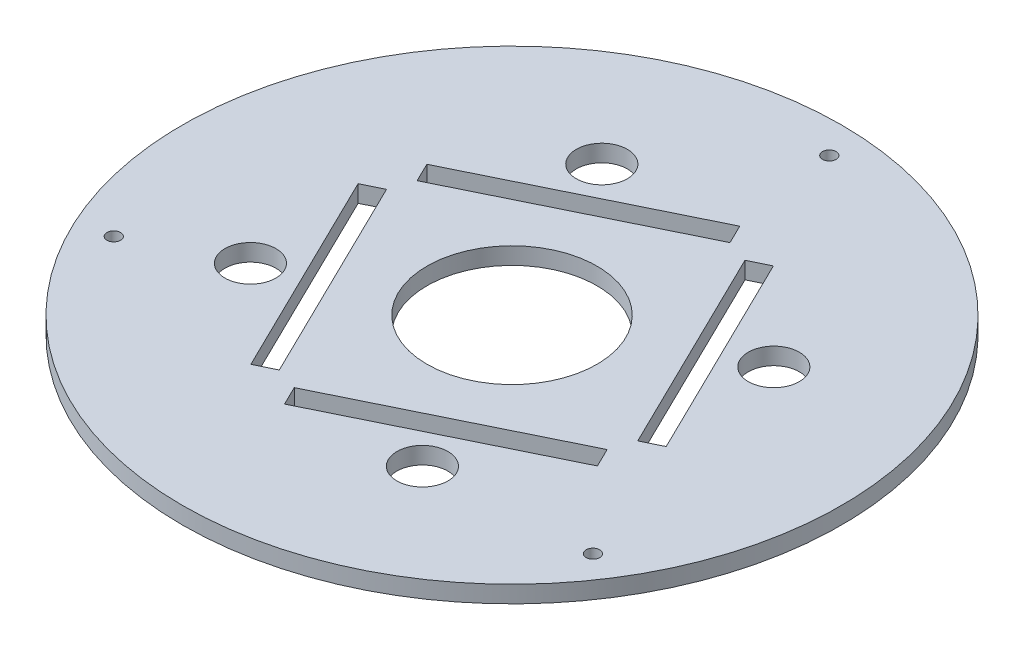
SolidWorks part; units mm, degrees
ref_plane "前视基准面" through (0, 0, 0) normal (0, 0, 1) x (1, 0, 0)
ref_plane "上视基准面" through (0, 0, 0) normal (0, 1, 0) x (1, 0, 0)
ref_plane "右视基准面" through (0, 0, 0) normal (1, 0, 0) x (0, 0, -1)
sketch "草图1" plane through (0, 0, 0) normal (0, 1, 0) x (1, 0, 0)
  circle A0 centre (0, 0) radius 77.5
  circle A1 centre (4.7844, 69.8363) radius 1.6
  circle A2 centre (-62.8722, -30.7747) radius 1.6
  circle A3 centre (58.0878, -39.0616) radius 1.6
  dimension "D1" = 155
extrude "凸台-拉伸1" add sketch "草图1" along normal blind 4
sketch "草图3" plane through (0, 4, 0) normal (0, 1, 0) x (1, 0, 0)
  circle A0 centre (0, 0) radius 20
  dimension "D1" = 40
extrude "切除-拉伸2" cut sketch "草图3" against normal through all both and the other way through all
sketch "草图4" plane through (0, 0, 0) normal (0, -1, 0) x (1, 0, 0)
  line L0 (0.002, -0.0288) -> (41.318, -20.2522) construction
  line L1 (0.002, -0.0288) -> (20.2254, 41.2872) construction
  line L2 (38.5519, 16.1767) -> (40.7501, 20.6676)
  line L3 (40.7501, 20.6676) -> (-8.6495, 44.8477)
  line L4 (-8.6495, 44.8477) -> (-10.8477, 40.3568)
  line L5 (-10.8477, 40.3568) -> (38.5519, 16.1767)
  line L6 (16.0503, 32.7576) -> (13.8521, 28.2668)
  line L7 (40.3876, 10.8209) -> (16.2075, -38.5787)
  line L8 (16.2075, -38.5787) -> (20.6984, -40.7769)
  line L9 (20.6984, -40.7769) -> (44.8785, 8.6227)
  line L10 (44.8785, 8.6227) -> (40.3876, 10.8209)
  line L11 (10.8517, -40.4144) -> (-38.5479, -16.2343)
  line L12 (-38.5479, -16.2343) -> (-40.7461, -20.7252)
  line L13 (-40.7461, -20.7252) -> (8.6535, -44.9053)
  line L14 (8.6535, -44.9053) -> (10.8517, -40.4144)
  line L15 (-40.3836, -10.8785) -> (-16.2035, 38.5211)
  line L16 (-16.2035, 38.5211) -> (-20.6944, 40.7193)
  line L17 (-20.6944, 40.7193) -> (-44.8745, -8.6803)
  line L18 (-44.8745, -8.6803) -> (-40.3836, -10.8785)
  circle A0 centre (41.318, -20.2522) radius 6
  circle A1 centre (0.002, -0.0288) radius 46 construction
  circle A2 centre (-20.2214, -41.3448) radius 6
  circle A3 centre (-41.314, 20.1946) radius 6
  circle A4 centre (20.2254, 41.2872) radius 6
  point P16 (0.002, -0.0288)
  point P35 (0.002, -0.0288)
  dimension "D1" = 12
  dimension "D2" = 4
  dimension "D3" = 5
  dimension "D4" = 55
  dimension "D5" = 4
extrude "切除-拉伸3" cut sketch "草图4" against normal through all both and the other way through all contours A3 | L17 L18 L15 L16 | L6 L3 L4 L5 | A4 | L3 L6 L5 L2 | L9 L10 L7 L8 | A0 | L13 L14 L11 L12 | A2
